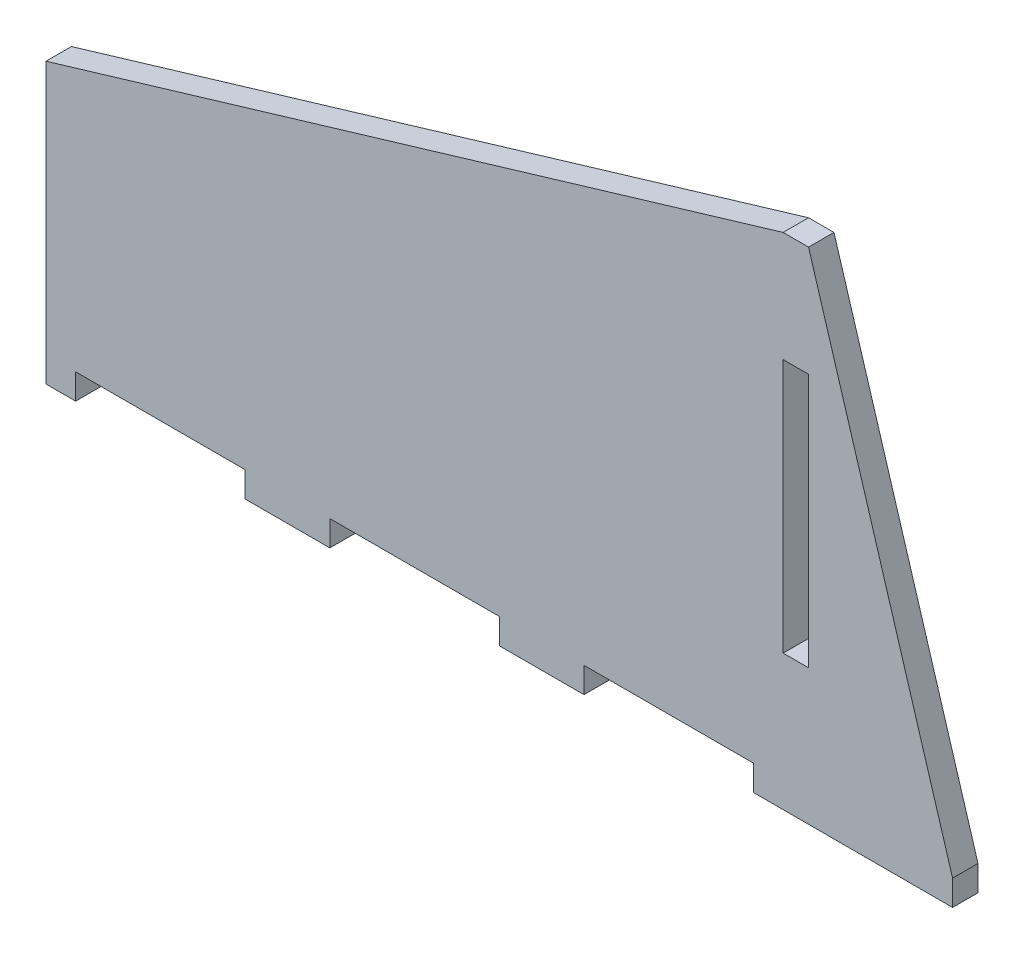
SolidWorks part; units mm, degrees
ref_plane "Front Plane" through (0, 0, 0) normal (0, 0, 1) x (1, 0, 0)
ref_plane "Top Plane" through (0, 0, 0) normal (0, 1, 0) x (1, 0, 0)
ref_plane "Right Plane" through (0, 0, 0) normal (1, 0, 0) x (0, 0, -1)
sketch "Sketch1" plane through (0, 0, 0) normal (0, 0, 1) x (1, 0, 0)
  line L0 (-90, 0) -> (-86.5, 0)
  line L1 (17, 0) -> (17, 3)
  line L2 (17, 3) -> (0, 59)
  line L3 (0, 59) -> (-3, 59)
  line L4 (-3, 59) -> (-90, 33)
  line L5 (-90, 33) -> (-90, 0)
  line L6 (-66.5, 3) -> (-66.5, 0)
  line L7 (-6.5, 0) -> (-6.5, 3) construction
  line L8 (-66.5, 0) -> (-56.5, 0)
  line L9 (-56.5, 0) -> (-56.5, 3)
  line L10 (-56.5, 3) -> (-36.5, 3)
  line L11 (-36.5, 3) -> (-36.5, 0)
  line L12 (-36.5, 0) -> (-26.5, 0)
  line L13 (-26.5, 0) -> (-26.5, 3)
  line L14 (-3, 46) -> (-3, 16)
  line L15 (-3, 16) -> (0, 16)
  line L16 (0, 16) -> (0, 46)
  line L17 (0, 46) -> (-3, 46)
  line L24 (-66.5, 3) -> (-86.5, 3) construction
  line L25 (-86.5, 3) -> (-86.5, 0) construction
  line L27 (-6.5, 0) -> (-6.5, 3)
  line L28 (-6.5, 3) -> (-26.5, 3)
  line L36 (-66.5, 3) -> (-86.5, 3)
  line L37 (-86.5, 3) -> (-86.5, 0)
  line L40 (-6.5, 0) -> (17, 0)
  line L42 (0, 59) -> (0, 0) construction
  point P23 (-26.3242, 2.5982)
  dimension "D1" = 107
  dimension "D2" = 59
  dimension "D3" = 17
  dimension "D4" = 33
  dimension "D5" = 3
  dimension "D6" = 20
extrude "Boss-Extrude1" add sketch "Sketch1" along normal blind 3
